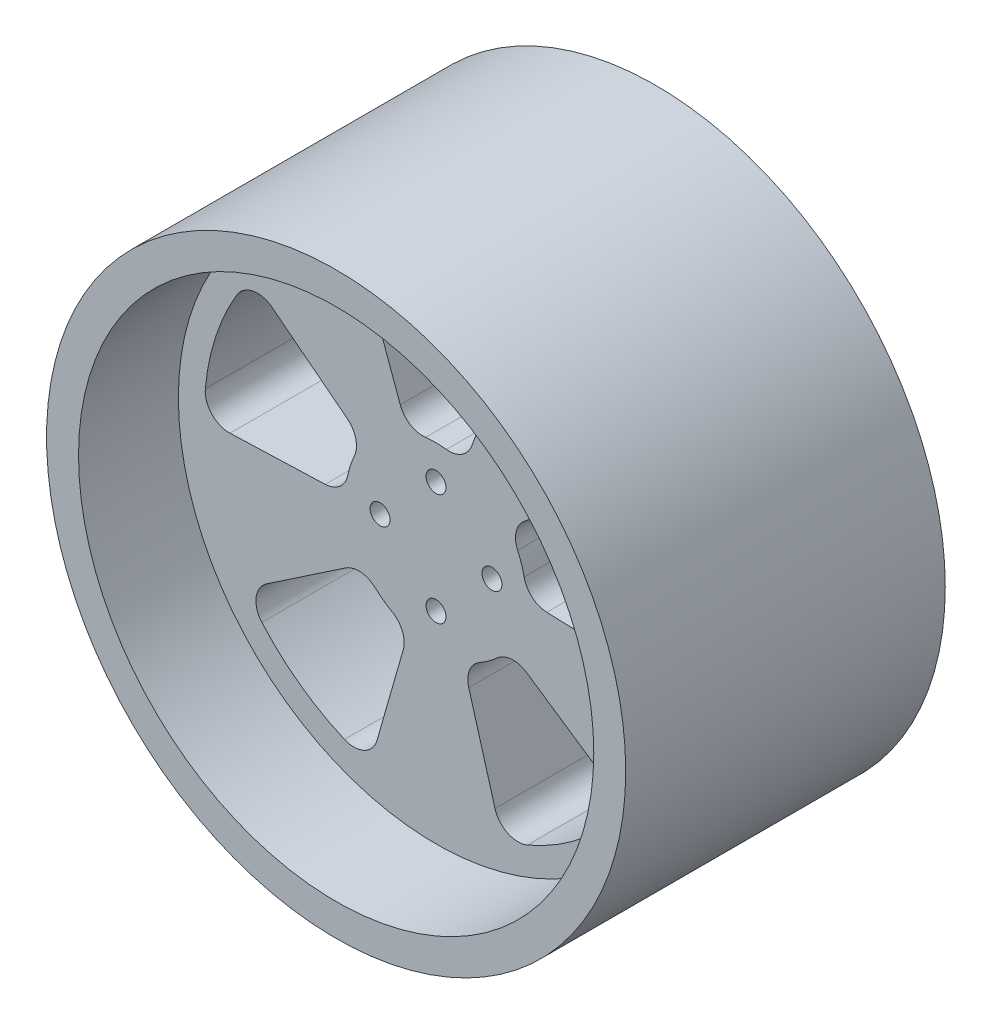
SolidWorks part; units mm, degrees
material "PA Type 6"
ref_plane "Front Plane" through (0, 0, 0) normal (0, 0, 1) x (1, 0, 0)
ref_plane "Top Plane" through (0, 0, 0) normal (0, 1, 0) x (1, 0, 0)
ref_plane "Right Plane" through (0, 0, 0) normal (1, 0, 0) x (0, 0, -1)
sketch "Sketch1" plane through (0, 0, 0) normal (0, 0, 1) x (1, 0, 0)
  circle A0 centre (0, 0) radius 72.5
  circle A1 centre (0, 0) radius 64.5
  dimension "D1" = 145
  dimension "D2" = 8
extrude "Boss-Extrude1" add sketch "Sketch1" along normal mid plane 80
sketch "Sketch4" plane through (0, 0, 0) normal (0, 0, 1) x (1, 0, 0)
  circle A0 centre (0, 0) radius 64.5
  dimension "D1" = 129
extrude "Boss-Extrude3" add sketch "Sketch4" along normal mid plane 30
sketch "Sketch3" plane through (0, 0, 0) normal (0, 0, 1) x (1, 0, 0)
  line L0 (0, 22.5) -> (0, 58) construction
  line L1 (8.9423, 26.2557) -> (17.1001, 48.6689)
  line L2 (-8.9423, 26.2557) -> (-17.1001, 48.6689)
  line L3 (22.2073, 16.6181) -> (41.0027, 31.3027)
  line L4 (27.734, -0.3912) -> (51.5711, -1.2236)
  line L5 (22.6672, -15.9851) -> (42.4411, -29.3228)
  line L6 (8.1982, -26.4975) -> (14.7726, -49.4252)
  line L7 (-8.1982, -26.4975) -> (-14.7726, -49.4252)
  line L8 (-22.6672, -15.9851) -> (-42.4411, -29.3228)
  line L9 (-27.734, -0.3912) -> (-51.5711, -1.2236)
  line L10 (-22.2073, 16.6181) -> (-41.0027, 31.3027)
  arc A3 (2.6086, 22.3483) -> (-2.6086, 22.3483) centre (0, 0) ccw
  arc A4 (12.7845, 56.5735) -> (-12.7845, 56.5735) centre (0, 0) ccw
  arc A5 (57.7552, 5.3234) -> (49.8539, 29.6409) centre (0, 0) ccw
  arc A6 (22.0606, 4.4251) -> (20.4484, 9.3869) centre (0, 0) ccw
  arc A7 (22.9102, -53.2834) -> (43.5959, -38.2544) centre (0, 0) ccw
  arc A8 (11.0256, -19.6134) -> (15.2464, -16.5469) centre (0, 0) ccw
  arc A9 (-43.5959, -38.2544) -> (-22.9102, -53.2834) centre (0, 0) ccw
  arc A10 (-15.2464, -16.5469) -> (-11.0256, -19.6134) centre (0, 0) ccw
  arc A11 (-49.8539, 29.6409) -> (-57.7552, 5.3234) centre (0, 0) ccw
  arc A12 (-20.4484, 9.3869) -> (-22.0606, 4.4251) centre (0, 0) ccw
  arc A16 (49.8539, 29.6409) -> (41.0027, 31.3027) centre (44.6966, 26.5746) ccw
  arc A17 (22.2073, 16.6181) -> (20.4484, 9.3869) centre (25.9013, 11.8901) ccw
  arc A18 (22.0606, 4.4251) -> (27.734, -0.3912) centre (27.9434, 5.6051) ccw
  arc A19 (22.6672, -15.9851) -> (15.2464, -16.5469) centre (19.3121, -20.9594) ccw
  arc A20 (43.5959, -38.2544) -> (42.4411, -29.3228) centre (39.086, -34.297) ccw
  arc A21 (22.9102, -53.2834) -> (14.7726, -49.4252) centre (20.5402, -47.7713) cw
  arc A22 (11.0256, -19.6134) -> (8.1982, -26.4975) centre (13.9658, -24.8437) ccw
  arc A23 (-8.1982, -26.4975) -> (-11.0256, -19.6134) centre (-13.9658, -24.8437) ccw
  arc A24 (-22.9102, -53.2834) -> (-14.7726, -49.4252) centre (-20.5402, -47.7713) ccw
  arc A25 (-43.5959, -38.2544) -> (-42.4411, -29.3228) centre (-39.086, -34.297) cw
  arc A26 (-15.2464, -16.5469) -> (-22.6672, -15.9851) centre (-19.3121, -20.9594) ccw
  arc A27 (-27.734, -0.3912) -> (-22.0606, 4.4251) centre (-27.9434, 5.6051) ccw
  arc A28 (-57.7552, 5.3234) -> (-51.5711, -1.2236) centre (-51.7805, 4.7727) ccw
  arc A29 (-49.8539, 29.6409) -> (-41.0027, 31.3027) centre (-44.6966, 26.5746) cw
  arc A30 (-20.4484, 9.3869) -> (-22.2073, 16.6181) centre (-25.9013, 11.8901) ccw
  arc A31 (8.9423, 26.2557) -> (2.6086, 22.3483) centre (3.3042, 28.3078) cw
  arc A32 (-8.9423, 26.2557) -> (-2.6086, 22.3483) centre (-3.3042, 28.3078) ccw
  arc A33 (17.1001, 48.6689) -> (12.7845, 56.5735) centre (11.4619, 50.721) ccw
  arc A34 (-17.1001, 48.6689) -> (-12.7845, 56.5735) centre (-11.4619, 50.721) cw
  arc A35 (57.7552, 5.3234) -> (51.5711, -1.2236) centre (51.7805, 4.7727) cw
  point P27 (0, 0)
  point P64 (0, 0)
  dimension "D1" = 20
  dimension "D3" = 5
  dimension "D4" = 58
  dimension "D5" = 6
  dimension "D6" = 6
  dimension "D7" = 22.5
  dimension "D2" = 20
extrude "Cut-Extrude1" cut sketch "Sketch3" against normal mid plane 30
sketch "Sketch6" plane through (0, 0, 15) normal (0, 0, 1) x (1, 0, 0)
  circle A0 centre (0, 0) radius 14 construction
  circle A1 centre (0, 14) radius 2.5
  circle A2 centre (14, 0) radius 2.5
  circle A3 centre (0, -14) radius 2.5
  circle A4 centre (-14, 0) radius 2.5
  point P14 (0, 0)
  dimension "D1" = 4
  dimension "D2" = 28
extrude "Cut-Extrude2" cut sketch "Sketch6" against normal blind 30
